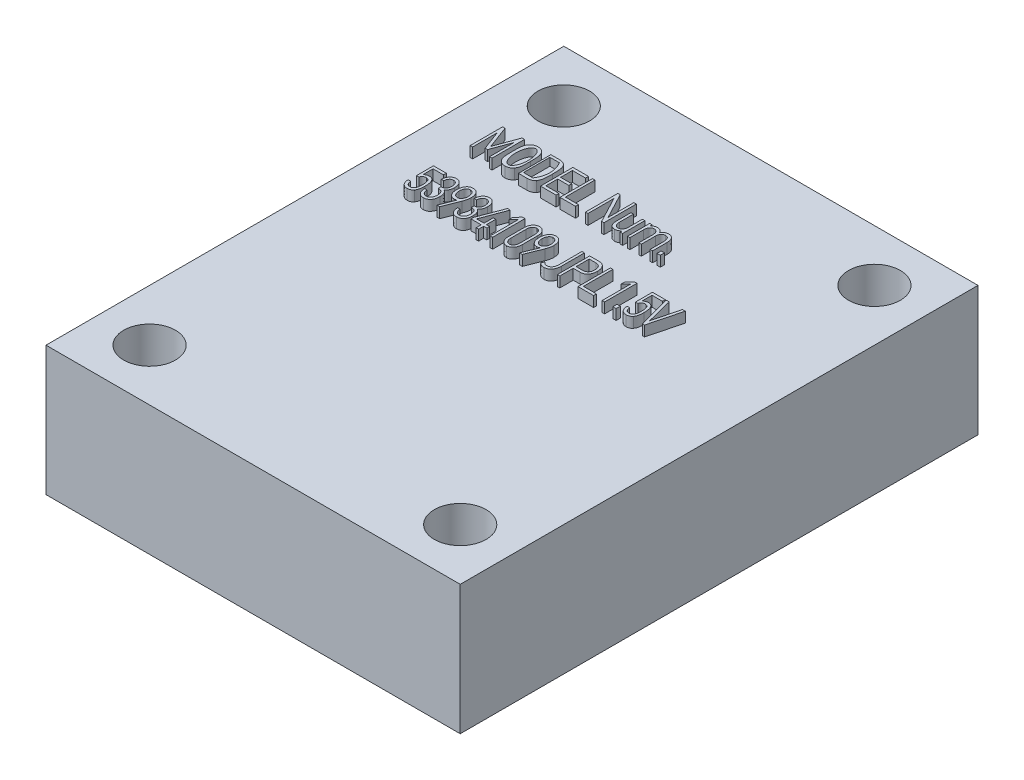
SolidWorks part; units mm, degrees
material "ABS"
ref_plane "Front Plane" through (0, 0, 0) normal (0, 0, 1) x (1, 0, 0)
ref_plane "Top Plane" through (0, 0, 0) normal (0, 1, 0) x (1, 0, 0)
ref_plane "Right Plane" through (0, 0, 0) normal (1, 0, 0) x (0, 0, -1)
sketch "Sketch1" plane through (0, 0, 0) normal (0, 1, 0) x (1, 0, 0)
  line L1 (-20.32, -25.4) -> (20.32, -25.4)
  line L2 (-20.32, -25.4) -> (-20.32, 25.4)
  line L3 (-20.32, 25.4) -> (20.32, 25.4)
  line L4 (20.32, -25.4) -> (20.32, 25.4)
  line L5 (-20.32, -25.4) -> (20.32, 25.4) construction
  line L6 (-20.32, 25.4) -> (20.32, -25.4) construction
  point P0 (0, 0)
  dimension "D1" = 40.64
  dimension "D2" = 50.8
extrude "Boss-Extrude1" add sketch "Sketch1" along normal blind 12.7
sketch "Sketch2" plane through (0, 12.7, 0) normal (0, 1, 0) x (1, 0, 0)
  line L8 (15.24, -20.32) -> (15.24, 20.32)
  line L9 (15.24, 20.32) -> (-15.24, 20.32)
  line L10 (-15.24, 20.32) -> (-15.24, -20.32)
  line L11 (-15.24, -20.32) -> (15.24, -20.32)
  line L12 (15.24, -20.32) -> (15.24, 20.32) construction
  line L13 (15.24, 20.32) -> (-15.24, 20.32) construction
  line L14 (-15.24, 20.32) -> (-15.24, -20.32) construction
  line L15 (-15.24, -20.32) -> (15.24, -20.32) construction
  circle A0 centre (-15.24, 20.32) radius 2.54
  circle A1 centre (15.24, 20.32) radius 2.54
  circle A2 centre (15.24, -20.32) radius 2.54
  circle A3 centre (-15.24, -20.32) radius 2.54
  dimension "D2" = 5.08
  dimension "D3" = 5.08
  dimension "D4" = 5.08
  dimension "D5" = 5.08
  dimension "D1" = 5.08
extrude "Cut-Extrude1" cut sketch "Sketch2" against normal through all
sketch "Sketch3" plane through (0, 12.7, 0) normal (0, 1, 0) x (1, 0, 0)
  text T0 "MODEL Num.\r\n53934109 JPL1.5V" font "DINPro-Regular" height 3.175
extrude "Boss-Extrude2" add sketch "Sketch3" along normal blind 1.016
sketch "Sketch4" plane through (0, 13.716, 0) normal (0, 1, 0) x (1, 0, 0)
  ellipse E0 centre (-11.967, 12.9542) end of major axis (-11.967, 14.3053) minor radius 0.6273
extrude "Cut-Extrude2" cut sketch "Sketch4" against normal blind 0.762
sketch "Sketch5" plane through (0, 13.716, 0) normal (0, 1, 0) x (1, 0, 0)
  line L0 (-10.5471, 14.2667) -> (-10.5471, 11.6768)
  line L1 (-10.5471, 11.6768) -> (-9.626, 11.6768)
  line L2 (-10.5471, 14.2667) -> (-9.626, 14.2667)
  arc A0 (-9.626, 14.2667) -> (-9.626, 11.6768) centre (-11.5923, 12.9717) cw
extrude "Cut-Extrude3" cut sketch "Sketch5" against normal blind 0.762
